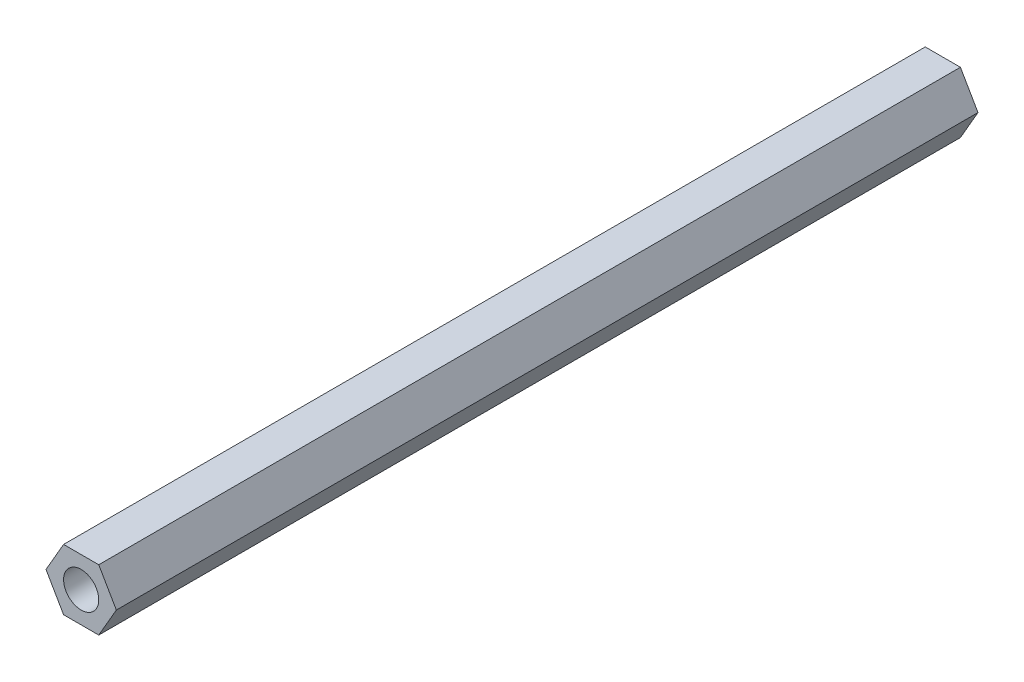
SolidWorks part; units mm, degrees
ref_plane "前视基准面" through (0, 0, 0) normal (0, 0, 1) x (1, 0, 0)
ref_plane "上视基准面" through (0, 0, 0) normal (0, 1, 0) x (1, 0, 0)
ref_plane "右视基准面" through (0, 0, 0) normal (1, 0, 0) x (0, 0, -1)
sketch "草图1" plane through (0, 0, 0) normal (0, 0, 1) x (1, 0, 0)
  line L1 (-25.8, 29.8) -> (-27.8, 33.2641)
  line L2 (-27.8, 33.2641) -> (-31.8, 33.2641)
  line L3 (-31.8, 33.2641) -> (-33.8, 29.8)
  line L4 (-33.8, 29.8) -> (-31.8, 26.3359)
  line L5 (-31.8, 26.3359) -> (-27.8, 26.3359)
  line L6 (-27.8, 26.3359) -> (-25.8, 29.8)
  circle A0 centre (-29.8, 29.8) radius 3.4641 construction
  circle A1 centre (-29.8, 29.8) radius 2
  dimension "D1" = 4
  dimension "D2" = 4
extrude "凸台-拉伸1" add sketch "草图1" along normal blind 98
